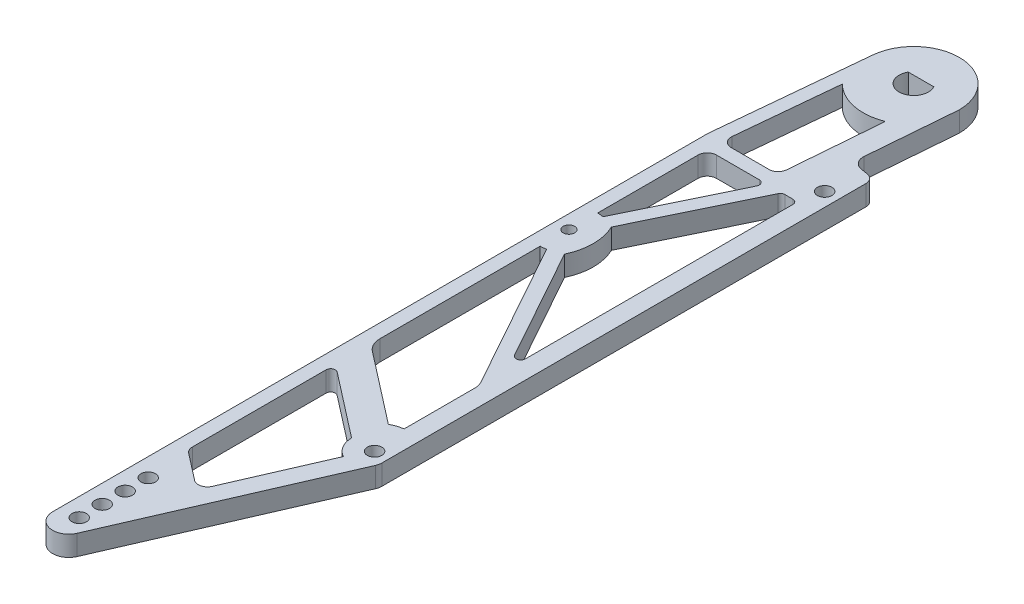
SolidWorks part; units mm, degrees
material "6061-T6 (SS)"
ref_plane "X-Y Datum" through (0, 0, 0) normal (0, 0, 1) x (1, 0, 0)
ref_plane "X-Z Datum" through (0, 0, 0) normal (0, 1, 0) x (1, 0, 0)
ref_plane "Y-Z Datum" through (0, 0, 0) normal (1, 0, 0) x (0, 0, -1)
other "Graphic1" [suppressed]
other "Graphic (Closed) -1" [suppressed]
sketch "Sketch2" plane through (0, 0, 0) normal (0, 1, 0) x (1, 0, 0)
  line L5 (13.4859, -162.4108) -> (-11.43, -143.082) construction
  line L8 (0, 0) -> (0, -24.13) construction
  line L11 (15.1556, -28.0184) -> (13.2387, -27.713)
  line L15 (-16.51, -221.3289) -> (-16.51, -40.4661)
  line L22 (-7.9887, -223.1013) -> (16.9799, -165.6775)
  line L23 (17.2959, -164.1583) -> (17.2959, -30.5268)
  line L33 (10.4385, -167.9818) -> (-0.5342, -193.2173)
  line L44 (-7.4473, -76.0744) -> (7.5755, -45.0536)
  line L45 (8.7185, -44.3372) -> (10.9459, -44.3372)
  line L46 (12.2159, -45.6072) -> (12.2159, -119.4928)
  line L47 (9.8359, -120.11) -> (-7.4473, -89.0256)
  line L49 (-12.4315, -37.7433) -> (-9.7554, -9.9996)
  line L51 (5.1277, -12.9949) -> (3.0693, -38.194)
  line L53 (0.5377, -40.5272) -> (-9.9032, -40.5272)
  line L56 (1.663, -44.3372) -> (-10.16, -44.3372)
  line L57 (13.7382, -24.5776) -> (0, 0) construction
  line L58 (10.5738, -24.3191) -> (12.5603, 0)
  line L59 (-12.7, -149.6154) -> (-12.7, -186.5441)
  line L63 (7.1359, -162.4108) -> (-10.6516, -148.612)
  line L64 (-12.7, -74.6125) -> (-12.7, -46.8772)
  line L65 (2.8061, -46.1607) -> (-11.056, -74.7846)
  line L66 (-16.4983, -40.2222) -> (-12.5023, 1.2059)
  line L67 (-4.4204, -194.2114) -> (-11.7169, -188.551)
  line L68 (5.8058, -44.3372) -> (-12.7, -82.55) construction
  line L69 (-1.7326, -64.2739) -> (-5.1616, -62.6133) construction
  line L70 (8.9236, -154.0495) -> (-10.7338, -138.8001)
  line L71 (12.2159, -152.9708) -> (12.2159, -133.548)
  line L72 (11.5758, -131.0794) -> (-11.086, -90.3217)
  line L75 (-12.7, -134.7862) -> (-12.7, -90.4875)
  line L76 (-3.5217, 2) -> (3.5217, 2)
  circle A0 centre (0, 0) radius 4.05
  circle A2 centre (-11.43, -219.075) radius 2
  circle A3 centre (-11.43, -212.725) radius 2
  circle A4 centre (-11.43, -206.375) radius 2
  circle A5 centre (-11.43, -200.025) radius 2
  circle A7 centre (0, 0) radius 12.5603 construction
  circle A8 centre (-12.7, -82.55) radius 1.5875
  circle A12 centre (13.4859, -38.1) radius 2
  arc A13 (-12.5023, 1.2059) -> (12.5603, 0) centre (0, 0) cw
  arc A14 (-7.4473, -89.0256) -> (-7.4473, -76.0744) centre (-20.962, -82.55) ccw
  circle A16 centre (24.0125, -14.7036) radius 3.175 construction
  arc A17 (24.0125, -14.7036) -> (13.7382, -24.5776) centre (0, 0) cw construction
  circle A18 centre (13.7382, -24.5776) radius 3.175 construction
  arc A19 (13.2387, -27.713) -> (10.5738, -24.3191) centre (13.7382, -24.5776) cw
  arc A20 (15.1556, -28.0184) -> (17.2959, -30.5268) centre (14.7559, -30.5268) cw
  circle A21 centre (13.4859, -162.4108) radius 2
  arc A24 (10.4385, -167.9818) -> (7.1359, -162.4108) centre (13.4859, -162.4108) cw
  arc A25 (-16.51, -221.3289) -> (-7.9887, -223.1013) centre (-12.065, -221.3289) ccw
  arc A26 (-12.7, -74.6125) -> (-11.056, -74.7846) centre (-12.7, -82.55) cw
  arc A28 (5.1277, -12.9949) -> (-9.7554, -9.9996) centre (0, 0) cw
  arc A31 (-10.16, -44.3372) -> (-12.7, -46.8772) centre (-10.16, -46.8772) ccw
  arc A32 (-12.4315, -37.7433) -> (-9.9032, -40.5272) centre (-9.9032, -37.9872) ccw
  arc A33 (0.5377, -40.5272) -> (3.0693, -38.194) centre (0.5377, -37.9872) ccw
  arc A36 (-12.7, -149.6154) -> (-10.6516, -148.612) centre (-11.43, -149.6154) cw
  arc A37 (9.8359, -120.11) -> (12.2159, -119.4928) centre (10.9459, -119.4928) ccw
  arc A38 (7.5755, -45.0536) -> (8.7185, -44.3372) centre (8.7185, -45.6072) cw
  arc A39 (10.9459, -44.3372) -> (12.2159, -45.6072) centre (10.9459, -45.6072) cw
  arc A40 (1.663, -44.3372) -> (2.8061, -46.1607) centre (1.663, -45.6072) cw
  arc A50 (17.2959, -164.1583) -> (16.9799, -165.6775) centre (13.4859, -164.1583) cw
  arc A52 (-16.4983, -40.2222) -> (-16.51, -40.4661) centre (-13.97, -40.4661) ccw
  arc A53 (-12.7, -186.5441) -> (-11.7169, -188.551) centre (-10.16, -186.5441) ccw
  arc A54 (-4.4204, -194.2114) -> (-0.5342, -193.2173) centre (-2.8635, -192.2045) ccw
  arc A55 (12.2159, -152.9708) -> (8.9236, -154.0495) centre (13.4859, -162.4108) ccw
  arc A56 (-11.086, -90.3217) -> (-12.7, -90.4875) centre (-12.7, -82.55) cw
  arc A57 (-12.7, -134.7862) -> (-10.7338, -138.8001) centre (-7.62, -134.7862) ccw
  arc A58 (11.5758, -131.0794) -> (12.2159, -133.548) centre (7.1359, -133.548) cw
  point P30 (17.2959, -28.3595)
  point P44 (-3.4471, -63.4436)
  point P45 (-1.8376, -196.215)
  point P48 (12.2159, -82.55)
  point P75 (-4.05, 0)
  point P88 (-12.7, -44.3372)
  point P91 (-12.7, -40.5272)
  point P104 (12.2159, -124.3904)
  point P107 (7.9224, -44.3372)
  point P110 (12.2159, -44.3372)
  point P120 (17.2959, -164.9508)
  dimension "D1" = 8.1
  dimension "D6" = 4
  dimension "D12" = 24.13
  dimension "D5" = 25.1206
  dimension "D14" = 3.175
  dimension "D19" = 4
  dimension "D20" = 6.35
  dimension "D24" = 3.81
  dimension "D50" = 14.986
  dimension "D51" = 8.262
  dimension "D42" = 3.81
  dimension "D62" = 6.35
  dimension "D63" = 29.204
  dimension "D27" = 2.54
  dimension "D44" = 4
  dimension "D18" = 4.445
  dimension "D34" = 3.81
  dimension "D36" = 6.35
  dimension "D33" = 13.97
  dimension "D38" = 3.81
  dimension "D39" = 8.89
  dimension "D48" = 2.54
  dimension "D49" = 1.27
  dimension "D52" = 3.81
  dimension "D53" = 3.81
  dimension "D54" = 9.525
  dimension "D58" = 2.54
  dimension "D59" = 3.81
  dimension "D64" = 2
  dimension "D29" = 7.9375
  dimension "D31" = 3.81
  dimension "D41" = 2.54
  dimension "D55" = 7.9375
  dimension "D57" = 5.08
  dimension "D7" = 6.35
  dimension "D8" = 6.35
  dimension "D9" = 6.35
  dimension "D10" = 5.08
  dimension "D11" = 5.08
  dimension "D13" = 4.1084
  dimension "D15" = 82.55
  dimension "D16" = 12.7
  dimension "D17" = 13.7382
  dimension "D21" = 136.5913
  dimension "D22" = 38.1
  dimension "D23" = 13.4859
  dimension "D25" = 5.08
  dimension "D26" = 3.81
  dimension "D28" = 40.5272
  dimension "D30" = 2.54
  dimension "D32" = 3.81
  dimension "D35" = 3.81
  dimension "D37" = 16.51
  dimension "D40" = 23.5
  dimension "D43" = 200.025
  dimension "D45" = 6.35
  dimension "D46" = 6.35
  dimension "D47" = 4.2935
  dimension "D56" = 3.81
  dimension "D60" = 24.0125
  dimension "D61" = 14.7036
extrude "Boss-Extrude1" add sketch "Sketch2" along normal blind 5.588 contours L76 A0 | L15 A52 L66 A13 L58 A19 L11 A20 L23 A50 L22 A25 | A32 L53 A33 L51 A28 L49 | A40 L56 A31 L64 A26 L65 | A14 L44 A38 L45 A39 L46 A37 L47 | A8 | L75 A56 L72 A58 L71 A55 L70 A57 | A36 L63 A24 L33 A54 L67 A53 L59 | A21 | A5 | A4 | A3 | A2 | A12
sketch "Sketch6" plane through (-16.51, 0, 0) normal (-1, 0, 0) x (0, 0, 1)
  line L0 (183.2289, 5.588) -> (183.2289, 0)
  line L1 (221.3289, 0) -> (40.4661, 0) construction
  line L2 (221.3289, 5.588) -> (40.4661, 5.588) construction
  line L3 (221.3289, 5.588) -> (221.3289, 0) construction
  point P2 (183.2289, 0)
  point P5 (183.2289, 5.588)
  dimension "D1" = 38.1
split line "Split Line2"
